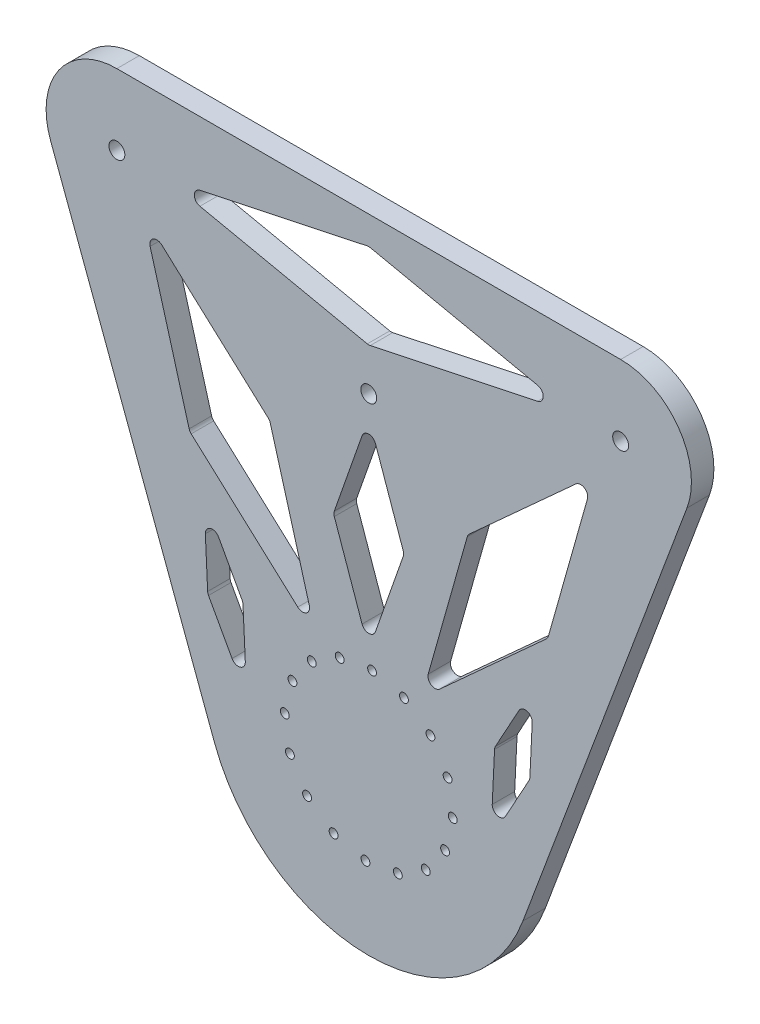
SolidWorks part; units mm, degrees
ref_plane "Front Plane" through (0, 0, 0) normal (0, 0, 1) x (1, 0, 0)
ref_plane "Top Plane" through (0, 0, 0) normal (0, 1, 0) x (1, 0, 0)
ref_plane "Right Plane" through (0, 0, 0) normal (1, 0, 0) x (0, 0, -1)
sketch "Sketch1" plane through (0, 0, 0) normal (0, 0, 1) x (1, 0, 0)
  line L0 (43.5664, -16.2548) -> (100, 135)
  line L1 (100, 135) -> (-100, 135)
  line L2 (-100, 135) -> (-43.5664, -16.2548)
  line L3 (0, 0) -> (0, 135) construction
  circle A0 centre (0, 0) radius 46.5 construction
  arc A1 (-43.5664, -16.2548) -> (43.5664, -16.2548) centre (0, 0) ccw
  dimension "D1" = 93
  dimension "D2" = 200
  dimension "D3" = 135
extrude "Boss-Extrude1" add sketch "Sketch1" along normal mid plane 6.35
fillet "Fillet1" radius 20 2 edges at (-100, 135, 0) (100, 135, 0)
sketch "Sketch2" plane through (0, 0, -3.175) normal (0, 0, -1) x (-1, 0, 0)
  line L0 (0, 135) -> (0, -46.5) construction
  line L1 (-71.1912, 135) -> (71.1912, 135) construction
  arc A0 (-43.5664, -16.2548) -> (43.5664, -16.2548) centre (0, 0) ccw construction
  circle A1 centre (-71.1912, 115) radius 2.25
  circle A2 centre (71.1912, 115) radius 2.25
  circle A3 centre (0, 91) radius 2.25
  arc A4 (-71.1912, 135) -> (-89.9295, 108.0087) centre (-71.1912, 115) ccw construction
  arc A5 (89.9295, 108.0087) -> (71.1912, 135) centre (71.1912, 115) ccw construction
  point P13 (0, 86.9888)
  dimension "D1" = 4.5
  dimension "D2" = 44
extrude "Cut-Extrude1" cut sketch "Sketch2" against normal through all
sketch "Sketch3" plane through (0, 0, -3.175) normal (0, 0, -1) x (-1, 0, 0)
  circle A0 centre (17.4402, -16.1215) radius 1.25 construction
  circle A1 centre (22.282, -8.2203) radius 1.25 construction
  circle A2 centre (9.9432, -21.5684) radius 1.25 construction
  circle A3 centre (0.9324, -23.7317) radius 1.25 construction
  circle A4 centre (-8.2203, -22.282) radius 1.25 construction
  circle A5 centre (-16.1215, -17.4402) radius 1.25 construction
  circle A6 centre (-21.5684, -9.9432) radius 1.25 construction
  circle A7 centre (-23.7317, -0.9324) radius 1.25 construction
  circle A8 centre (-22.282, 8.2203) radius 1.25 construction
  circle A9 centre (-17.4402, 16.1215) radius 1.25 construction
  circle A10 centre (-9.9432, 21.5684) radius 1.25 construction
  circle A11 centre (-0.9324, 23.7317) radius 1.25 construction
  circle A12 centre (8.2203, 22.282) radius 1.25 construction
  circle A13 centre (16.1215, 17.4402) radius 1.25 construction
  circle A14 centre (21.5684, 9.9432) radius 1.25 construction
  circle A15 centre (23.7317, 0.9324) radius 1.25 construction
  circle A16 centre (17.4402, -16.1215) radius 1.25
  circle A17 centre (22.282, -8.2203) radius 1.25
  circle A18 centre (9.9432, -21.5684) radius 1.25
  circle A19 centre (0.9324, -23.7317) radius 1.25
  circle A20 centre (-8.2203, -22.282) radius 1.25
  circle A21 centre (-16.1215, -17.4402) radius 1.25
  circle A22 centre (-21.5684, -9.9432) radius 1.25
  circle A23 centre (-23.7317, -0.9324) radius 1.25
  circle A24 centre (-22.282, 8.2203) radius 1.25
  circle A25 centre (-17.4402, 16.1215) radius 1.25
  circle A26 centre (-9.9432, 21.5684) radius 1.25
  circle A27 centre (-0.9324, 23.7317) radius 1.25
  circle A28 centre (8.2203, 22.282) radius 1.25
  circle A29 centre (16.1215, 17.4402) radius 1.25
  circle A30 centre (21.5684, 9.9432) radius 1.25
  circle A31 centre (23.7317, 0.9324) radius 1.25
extrude "Cut-Extrude2" cut sketch "Sketch3" against normal through all both and the other way through all
sketch "Sketch4" plane through (0, 0, 3.175) normal (0, 0, 1) x (1, 0, 0)
  line L0 (-63.6967, 102.8937) -> (-50.6079, 56.4866)
  line L1 (-50.6079, 56.4866) -> (-14.9058, 24.0783)
  line L4 (0, 0) -> (-71.1912, 115) construction
  line L5 (0, 0) -> (71.1912, 115) construction
  line L6 (-63.6967, 102.8937) -> (-27.9946, 70.4854)
  line L7 (-27.9946, 70.4854) -> (-14.9058, 24.0783)
  line L8 (0, 0) -> (0, 135) construction
  line L9 (71.1912, 135) -> (-71.1912, 135) construction
  line L10 (63.6967, 102.8937) -> (50.6079, 56.4866)
  line L11 (50.6079, 56.4866) -> (14.9058, 24.0783)
  line L12 (27.9946, 70.4854) -> (14.9058, 24.0783)
  line L13 (63.6967, 102.8937) -> (27.9946, 70.4854)
  line L14 (0, 85.1838) -> (-9.9763, 56.7512)
  line L15 (-9.9763, 56.7512) -> (0, 28.3187)
  line L18 (9.9763, 56.7512) -> (0, 28.3187)
  line L19 (0, 85.1838) -> (9.9763, 56.7512)
  line L20 (-71.1912, 115) -> (71.1912, 115) construction
  line L21 (-56.9529, 115) -> (0, 127.0737)
  line L22 (-56.9529, 115) -> (0, 102.9263)
  line L23 (56.9529, 115) -> (0, 102.9263)
  line L24 (56.9529, 115) -> (0, 127.0737)
  line L25 (-46.6026, 42.2858) -> (-45.5127, 19.3978)
  line L26 (-45.5127, 19.3978) -> (-34.4825, -0.6866)
  line L29 (-34.4825, -0.6866) -> (-46.6026, 42.2858) construction
  line L30 (-35.5724, 22.2014) -> (-34.4825, -0.6866)
  line L31 (-46.6026, 42.2858) -> (-35.5724, 22.2014)
  line L32 (46.6026, 42.2858) -> (35.5724, 22.2014)
  line L33 (35.5724, 22.2014) -> (34.4825, -0.6866)
  line L34 (45.5127, 19.3978) -> (34.4825, -0.6866)
  line L35 (46.6026, 42.2858) -> (45.5127, 19.3978)
  circle A0 centre (0, 0) radius 28.3187 construction
  circle A1 centre (0, 208.5873) radius 117.5873 construction
  circle A2 centre (-71.1912, 115) radius 2.25 construction
  circle A3 centre (71.1912, 115) radius 2.25 construction
  circle A4 centre (0, 91) radius 2.25 construction
  circle A5 centre (-71.1912, 115) radius 2.25 construction
  circle A6 centre (71.1912, 115) radius 2.25 construction
  circle A7 centre (0, 91) radius 2.25 construction
  circle A8 centre (0, 208.5873) radius 123.4035 construction
  circle A9 centre (71.1912, 115) radius 14.2384 construction
  circle A10 centre (-71.1912, 115) radius 14.2384 construction
  point P38 (-50.4012, 19.9682)
  point P39 (-35.7756, 12.7396)
  point P40 (-39.5525, 3.2605)
  point P41 (-38.5488, 4.9121)
  point P44 (-46.1227, 16.3471)
  point P45 (-46.3927, 13.8681)
  point P46 (-48.5483, 41.737)
  point P47 (-47.4705, 19.1032)
  point P52 (-34.4825, -0.6866)
  dimension "D1" = 117.5873
extrude "Cut-Extrude3" cut sketch "Sketch4" against normal through all both and the other way through all
fillet "Fillet2" radius 2 24 edges at (50.6079, 56.4866, 0) (63.6967, 102.8937, 0) (27.9946, 70.4854, 0) (14.9058, 24.0783, 0) (-14.9058, 24.0783, 0) (-27.9946, 70.4854, 0) (-63.6967, 102.8937, 0) (-50.6079, 56.4866, 0) (9.9763, 56.7512, 0) (0, 85.1838, 0) (-9.9763, 56.7512, 0) (0, 28.3187, 0) (56.9529, 115, 0) (0, 102.9263, 0) (0, 127.0737, 0) (-56.9529, 115, 0) (45.5127, 19.3978, 0) (46.6026, 42.2858, 0) (35.5724, 22.2014, 0) (34.4825, -0.6866, 0) (-46.6026, 42.2858, 0) (-45.5127, 19.3978, 0) (-35.5724, 22.2014, 0) (-34.4825, -0.6866, 0)
